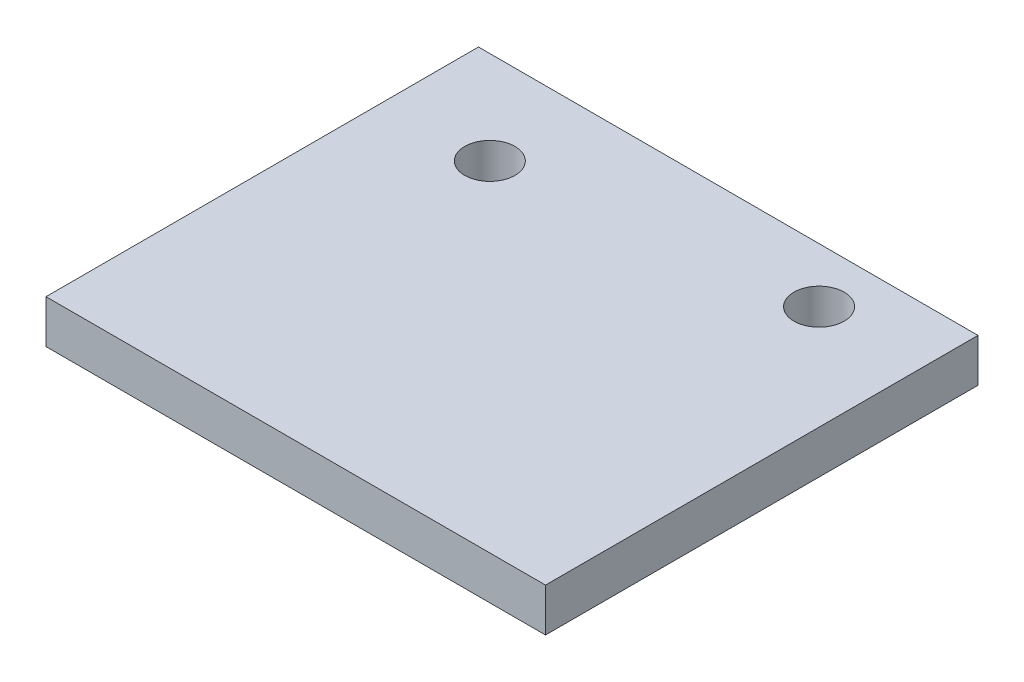
SolidWorks part; units mm, degrees
ref_plane "Płaszczyzna przednia" through (0, 0, 0) normal (0, 0, 1) x (1, 0, 0)
ref_plane "Płaszczyzna górna" through (0, 0, 0) normal (0, 1, 0) x (1, 0, 0)
ref_plane "Płaszczyzna prawa" through (0, 0, 0) normal (1, 0, 0) x (0, 0, -1)
sketch "Szkic1" plane through (0, 0, 0) normal (0, 1, 0) x (1, 0, 0)
  line L1 (0, 0) -> (462, 0)
  line L2 (0, 0) -> (0, 400)
  line L3 (0, 400) -> (462, 400)
  line L4 (462, 0) -> (462, 400)
  circle A0 centre (96.5, 314) radius 23.25
  circle A1 centre (365.5, 349.5) radius 23.25
  dimension "D7" = 46.5
  dimension "D8" = 46.5
  dimension "D1" = 462
  dimension "D2" = 400
  dimension "D3" = 314
  dimension "D4" = 349.5
  dimension "D5" = 96.5
  dimension "D6" = 269
extrude "Dodanie-wyciągnięcie1" add sketch "Szkic1" along normal blind 40
other "Grafika1" [suppressed]
other "Grafika (Zamknięta) -1"
sketch "Szkic2" [suppressed] plane through (0, 0, 0) normal (0, 1, 0) x (1, 0, 0)
  line L0 (155.0094, 255.3184) -> (365.2848, 88.7637)
  line L1 (365.2848, 88.7637) -> (391.8294, 50.7684)
  line L2 (384.5426, 27.8671) -> (46.4133, 26.6016)
  line L3 (23.8476, 58.5756) -> (108.6864, 249.0726)
  line L4 (0, 0) -> (0, 68.9853)
  line L5 (0, 68.9853) -> (86.3056, 249.0726)
  line L6 (67.9044, 278.2964) -> (46.3239, 314.6535)
  line L7 (46.3239, 314.6535) -> (52.4742, 338.5958)
  line L8 (52.4742, 338.5958) -> (108.6864, 366.7019)
  line L9 (108.6864, 366.7019) -> (154.4889, 321.9403)
  line L10 (154.4889, 321.9403) -> (328.8509, 179.8483)
  line L11 (354.3546, 200.1471) -> (356.3896, 289.4326)
  line L12 (356.3896, 289.4326) -> (317.8058, 344.3211)
  line L13 (317.8058, 344.3211) -> (317.8058, 366.7019)
  line L14 (317.8058, 366.7019) -> (346.799, 387.0826)
  line L15 (346.799, 387.0826) -> (384.5426, 387.0826)
  line L16 (384.5426, 387.0826) -> (415.155, 362.1359)
  line L17 (415.155, 362.1359) -> (415.155, 339.1162)
  line L18 (415.155, 339.1162) -> (374.3332, 289.0236)
  line L19 (374.3332, 289.0236) -> (376.231, 168.9181)
  line L20 (376.231, 168.9181) -> (462.0947, 58.5756)
  line L21 (462.0947, 58.5756) -> (462, 0)
  line L22 (462, 0) -> (0, 0)
  circle A0 centre (96.1948, 314.6535) radius 22.0884
  circle A1 centre (365.2848, 348.4849) radius 21.4348
  arc A2 (391.8294, 50.7684) -> (384.5426, 27.8671) centre (379.428, 42.1044) cw
  arc A3 (46.4133, 26.6016) -> (23.8476, 58.5756) centre (46.3239, 50.4884) cw
  arc A4 (108.6864, 249.0726) -> (155.0094, 255.3184) centre (133.7755, 237.899) cw
  arc A5 (86.3056, 249.0726) -> (67.9044, 278.2964) centre (67.9044, 257.8912) ccw
  arc A6 (328.8509, 179.8483) -> (354.3546, 200.1471) centre (339.3888, 192.7794) ccw
extrude "Dodanie-wyciągnięcie2" [suppressed] add sketch "Szkic2" along normal blind 40
